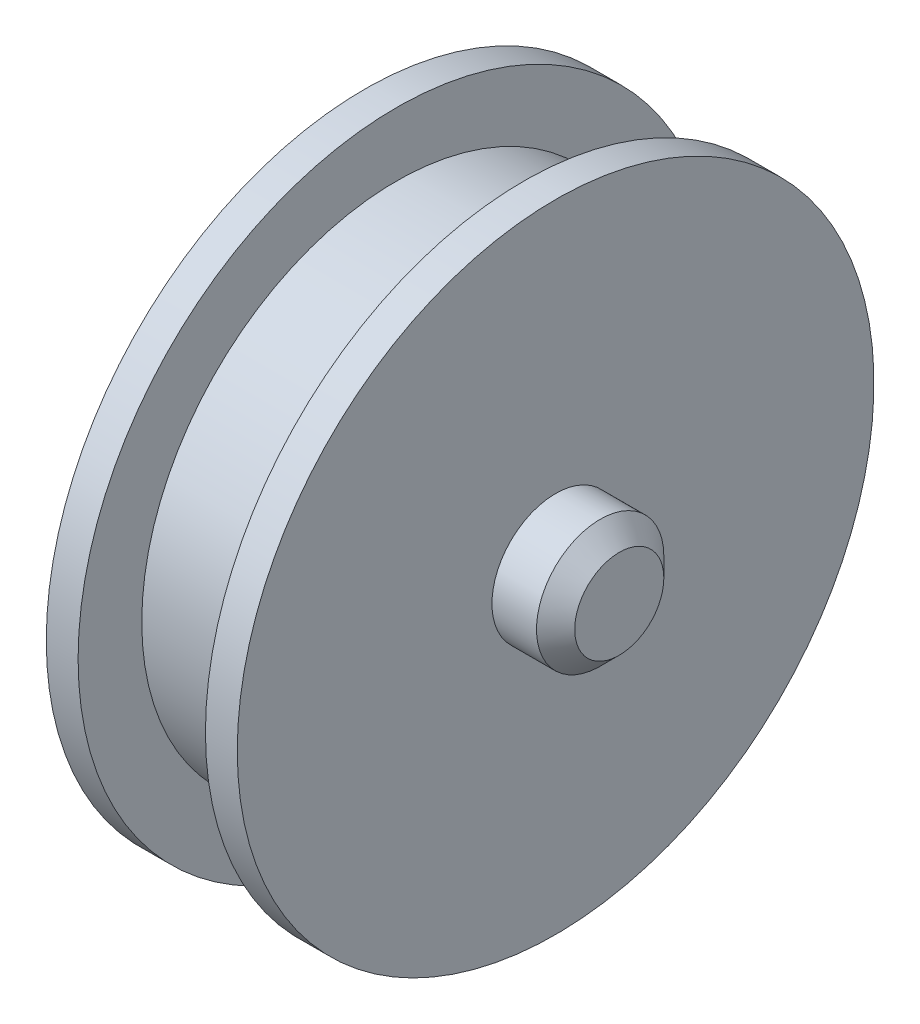
SolidWorks part; units mm, degrees
other "Marcação1"
sketch "Esboço3" plane through (-6.5, 5, 5) normal (-0.1539, 0.7423, 0.6521) x (0.9437, -0.0852, 0.3198)
ref_plane "Plano frontal" through (0, 0, 0) normal (0, 0, 1) x (1, 0, 0)
ref_plane "Plano superior" through (0, 0, 0) normal (0, 1, 0) x (1, 0, 0)
ref_plane "Plano direito" through (0, 0, 0) normal (1, 0, 0) x (0, 0, -1)
sketch "Esboço1" plane through (0, 0, 0) normal (0, 0, 1) x (1, 0, 0)
  line L0 (0, 0) -> (7.1551, 0) construction
  line L1 (-1.5, 0) -> (-1.5, 5) construction
  line L2 (-1.5, 5) -> (-1, 5)
  line L3 (-1, 5) -> (-1, 4)
  line L4 (-1, 4) -> (1, 4)
  line L5 (1, 4) -> (1, 5)
  line L6 (1, 5) -> (1.5, 5)
  line L7 (1.5, 5) -> (1.5, 0) construction
  line L8 (1.5, 0) -> (-1.5, 0) construction
  line L9 (-1, 4) -> (1, 6) construction
  line L10 (-1, 4) -> (-1, 6) construction
  line L11 (1, 6) -> (-1, 6) construction
  line L12 (1, 6) -> (1, 4) construction
  line L14 (-1.5, 5) -> (-1.5, 0)
  line L15 (1.5, 5) -> (1.5, 0)
  line L16 (-1.5, 0) -> (1.5, 0)
  circle A0 centre (0, 5) radius 1
  point P5 (0, 5)
  point P18 (0, 0)
  dimension "D1" = 5
  dimension "D2" = 3
  dimension "D3" = 2
  dimension "D4" = 1
revolve "Revolução2" add sketch "Esboço1" angle 360 about L0
sketch "Esboço2" plane through (-1.5, 0, 0) normal (-1, 0, 0) x (0, 0, 1)
  circle A0 centre (0, 0) radius 1
  dimension "D1" = 2
extrude "Ressalto-extrusão1" add sketch "Esboço2" along normal blind 1
sketch "Esboço4" plane through (1.5, 0, 0) normal (1, 0, 0) x (0, 0, -1)
  circle A0 centre (0, 0) radius 1
  dimension "D1" = 2
extrude "Ressalto-extrusão2" add sketch "Esboço4" along normal blind 1
chamfer "Chanfro1" distance 0.3 angle 45 1 edges at (-2.5, 0, 1)
chamfer "Chanfro2" distance 0.3 angle 45 1 edges at (2.5, 0, -1)
